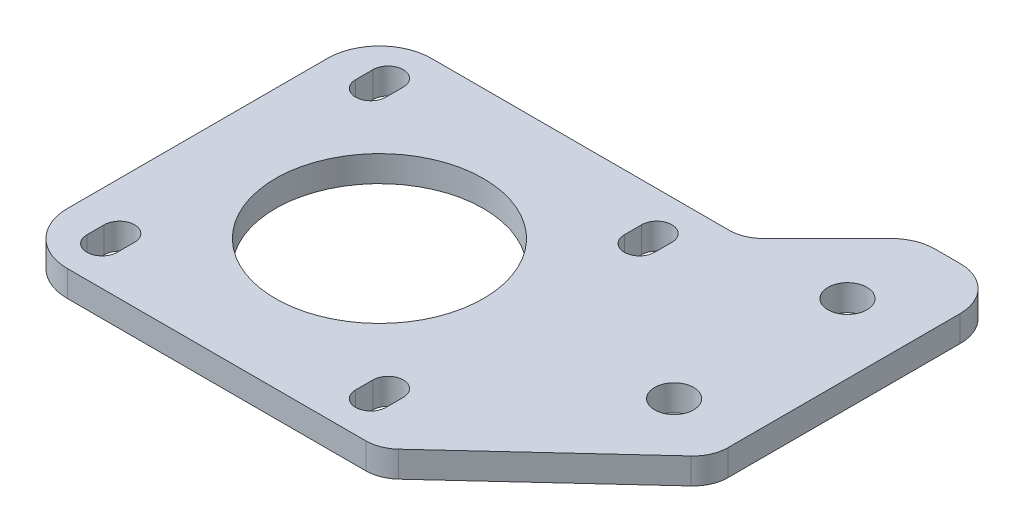
SolidWorks part; units mm, degrees
material "3.0205 (EN-AW 1200)"
ref_plane "Alzado" through (0, 0, 0) normal (0, 0, 1) x (1, 0, 0)
ref_plane "Planta" through (0, 0, 0) normal (0, 1, 0) x (1, 0, 0)
ref_plane "Vista lateral" through (0, 0, 0) normal (1, 0, 0) x (0, 0, -1)
ref_plane "Plano1" through (0, -1.5001, 0) normal (0, 1, 0) x (1, 0, 0)
sketch "Croquis1" plane through (0, -1.5001, 0) normal (0, 1, 0) x (1, 0, 0)
  line L0 (-251.75, -28.5) -> (-251.75, -30.5)
  line L1 (-255.25, -30.5) -> (-255.25, -28.5)
  line L2 (-282.75, -28.5) -> (-282.75, -30.5)
  line L3 (-286.25, -30.5) -> (-286.25, -28.5)
  line L4 (-255.25, 0.5) -> (-255.25, 2.5)
  line L5 (-251.75, 2.5) -> (-251.75, 0.5)
  line L6 (-286.25, 0.5) -> (-286.25, 2.5)
  line L7 (-282.75, 2.5) -> (-282.75, 0.5)
  line L8 (-284, -35) -> (-249.5632, -35)
  line L9 (-246.851, -33.9401) -> (-229.2878, -17.738)
  line L10 (-228, -14.7979) -> (-228, 12)
  line L11 (-233, 17) -> (-235.9289, 17)
  line L12 (-239.4645, 15.5355) -> (-246.8284, 8.1716)
  line L13 (-249.6569, 7) -> (-284, 7)
  line L14 (-290, 1) -> (-290, -29)
  arc A0 (-255.25, -28.5) -> (-251.75, -28.5) centre (-253.5, -28.5) cw
  arc A1 (-251.75, -30.5) -> (-255.25, -30.5) centre (-253.5, -30.5) cw
  arc A2 (-282.75, -30.5) -> (-286.25, -30.5) centre (-284.5, -30.5) cw
  arc A3 (-286.25, -28.5) -> (-282.75, -28.5) centre (-284.5, -28.5) cw
  arc A4 (-251.75, 0.5) -> (-255.25, 0.5) centre (-253.5, 0.5) cw
  arc A5 (-255.25, 2.5) -> (-251.75, 2.5) centre (-253.5, 2.5) cw
  arc A6 (-282.75, 0.5) -> (-286.25, 0.5) centre (-284.5, 0.5) cw
  arc A7 (-286.25, 2.5) -> (-282.75, 2.5) centre (-284.5, 2.5) cw
  circle A8 centre (-269, -14) radius 12
  circle A9 centre (-236, -13) radius 2.25
  circle A10 centre (-236, 7) radius 2.25
  arc A11 (-290, -29) -> (-284, -35) centre (-284, -29) ccw
  arc A12 (-249.5632, -35) -> (-246.851, -33.9401) centre (-249.5632, -31) ccw
  arc A13 (-229.2878, -17.738) -> (-228, -14.7979) centre (-232, -14.7979) ccw
  arc A14 (-228, 12) -> (-233, 17) centre (-233, 12) ccw
  arc A15 (-235.9289, 17) -> (-239.4645, 15.5355) centre (-235.9289, 12) ccw
  arc A16 (-246.8284, 8.1716) -> (-249.6569, 7) centre (-249.6569, 11) cw
  arc A17 (-284, 7) -> (-290, 1) centre (-284, 1) ccw
extrude "Saliente-Extruir1" add sketch "Croquis1" against normal blind 3
